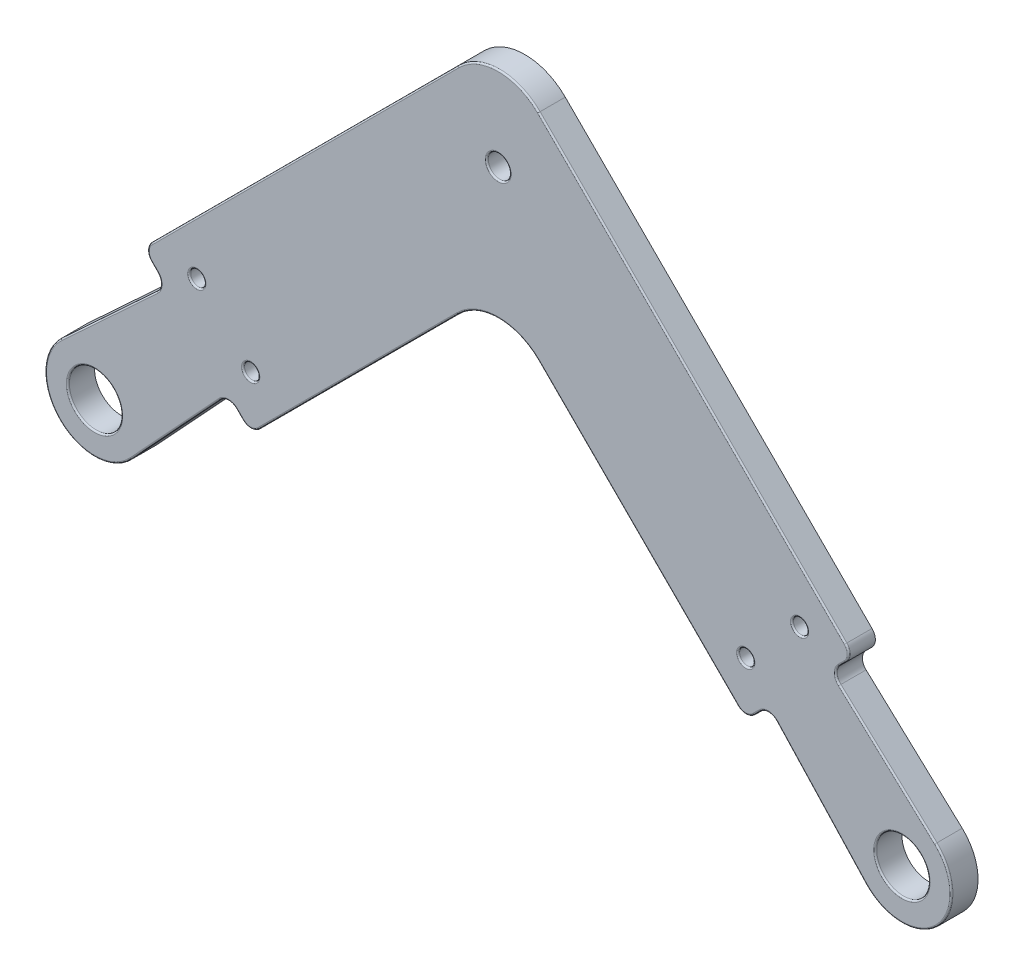
SolidWorks part; units mm, degrees
ref_plane "Front Plane" through (0, 0, 0) normal (0, 0, 1) x (1, 0, 0)
ref_plane "Top Plane" through (0, 0, 0) normal (0, 1, 0) x (1, 0, 0)
ref_plane "Right Plane" through (0, 0, 0) normal (1, 0, 0) x (0, 0, -1)
sketch "Sketch1" plane through (0, 0, 0) normal (0, 0, 1) x (1, 0, 0)
  line L0 (-106.0307, 0) -> (93.9693, 0) construction
  line L1 (-106.0307, 0) -> (-6.0307, 100) construction
  line L2 (-6.0307, 100) -> (93.9693, 0) construction
  line L3 (0, 0) -> (-53.0154, 53.0154) construction
  line L4 (-46.0307, 60) -> (33.9693, 60) construction
  line L5 (-6.0307, 100) -> (-6.0307, 60) construction
  circle A0 centre (-106.0307, 0) radius 20
  circle A1 centre (0, 0) radius 20
  circle A2 centre (93.9693, 0) radius 20
  dimension "D6" = 40
  dimension "D7" = 40
  dimension "D8" = 40
  dimension "D1" = 200
  dimension "D2" = 90
  dimension "D3" = 90
  dimension "D4" = 80
  dimension "D5" = 40
sketch "Sketch2" plane through (0, 0, 0) normal (0, 0, 1) x (1, 0, 0)
  line L0 (-62.5472, 43.4835) -> (-46.0307, 60) construction
  line L2 (-106.0307, 0) -> (-6.0307, 100) construction
  line L3 (-46.0307, 60) -> (33.9693, 60) construction
  line L4 (33.9693, 60) -> (80.5342, 13.435) construction
  line L5 (-6.0307, 100) -> (93.9693, 0) construction
  line L6 (-55.4762, 36.4124) -> (-41.8886, 50)
  line L7 (-41.8886, 50) -> (29.8271, 50)
  line L8 (29.8271, 50) -> (73.4632, 6.364)
  line L9 (-69.6183, 50.5546) -> (-50.1729, 70)
  line L10 (-50.1729, 70) -> (38.1114, 70)
  line L11 (38.1114, 70) -> (87.6053, 20.5061)
  line L12 (-55.4762, 36.4124) -> (-69.6183, 50.5546)
  line L13 (87.6053, 20.5061) -> (73.4632, 6.364)
  line L14 (98.8369, 5.0305) -> (85.2636, 18.1644)
  line L15 (88.8813, -4.8075) -> (76.0143, 8.8101)
  line L16 (85.2636, 18.1644) -> (76.0143, 8.8101)
  line L17 (84.0698, 24.0416) -> (69.9276, 9.8995) construction
  line L18 (-6.0307, 100) -> (-6.0307, 60) construction
  line L19 (-9.5307, 84.85) -> (-12.0307, 70)
  line L20 (-6.0307, 70) -> (-6.0307, 82.2198) construction
  line L21 (-2.5307, 84.85) -> (-0.0307, 70)
  circle A0 centre (93.9693, 0) radius 10 construction
  circle A1 centre (93.9693, 0) radius 3.5
  arc A2 (88.8813, -4.8075) -> (98.8369, 5.0305) centre (93.9693, 0) ccw
  circle A3 centre (93.9693, 0) radius 20 construction
  circle A4 centre (73.4632, 13.435) radius 1
  circle A5 centre (80.5342, 20.5061) radius 1
  circle A6 centre (-6.0307, 60) radius 1.5
  circle A7 centre (-6.0307, 84.85) radius 1.5
  arc A8 (-2.5307, 84.85) -> (-9.5307, 84.85) centre (-6.0307, 84.85) ccw
  circle A9 centre (-53.0154, 53.0154) radius 1.5
  point P45 (-6.0307, 70)
  dimension "D4" = 20
  dimension "D5" = 7
  dimension "D6" = 3
  dimension "D8" = 5
  dimension "D9" = 2
  dimension "D10" = 2
  dimension "D13" = 3
  dimension "D14" = 3
  dimension "D16" = 2
  dimension "D18" = 3
  dimension "D1" = 10
  dimension "D3" = 27.5
  dimension "D7" = 19
  dimension "D11" = 5
  dimension "D12" = 5
  dimension "D15" = 14.85
  dimension "D17" = 6
  dimension "D2" = 10
sketch "Sketch3" plane through (0, 0, 0) normal (0, 0, 1) x (1, 0, 0)
  line L0 (-94.5203, 11.5104) -> (-53.0154, 53.0154) construction
  line L1 (-106.0307, 0) -> (-6.0307, 100) construction
  line L2 (-53.0154, 53.0154) -> (-13.435, 13.435) construction
  line L3 (0, 0) -> (-53.0154, 53.0154) construction
  line L4 (-85.5246, 6.364) -> (-53.0154, 38.8732)
  line L5 (-53.0154, 38.8732) -> (-20.5061, 6.364)
  line L6 (-99.6668, 20.5061) -> (-53.0154, 67.1575)
  line L7 (-53.0154, 67.1575) -> (-6.364, 20.5061)
  line L8 (-95.851, 10.1797) -> (-53.0154, 53.0154) construction
  line L9 (-99.6668, 20.5061) -> (-85.5246, 6.364)
  line L10 (-20.5061, 6.364) -> (-6.364, 20.5061)
  line L11 (-102.9221, 17.2507) -> (-53.0154, 67.1575) construction
  line L12 (-88.78, 3.1086) -> (-53.0154, 38.8732) construction
  line L13 (-110.4492, 4.7673) -> (-96.685, 17.5243)
  line L14 (-106.0307, 0) -> (-96.685, 9.3457) construction
  line L15 (-101.2634, -4.4185) -> (-88.5064, 9.3457)
  line L16 (0, 0) -> (-13.435, 13.435) construction
  line L17 (-4.7673, -4.4185) -> (-17.5243, 9.3457)
  line L18 (4.4185, 4.7673) -> (-9.3457, 17.5243)
  line L19 (-96.1312, 24.0416) -> (-81.9891, 9.8995) construction
  line L20 (-9.8995, 24.0416) -> (-24.0416, 9.8995) construction
  circle A0 centre (-106.0307, 0) radius 10 construction
  circle A1 centre (-106.0307, 0) radius 3.5
  circle A2 centre (0, 0) radius 10 construction
  circle A4 centre (93.9693, 0) radius 10 construction
  circle A6 centre (0, 0) radius 3.5
  circle A7 centre (93.9693, 0) radius 3.5
  circle A8 centre (-106.0307, 0) radius 6.5
  circle A9 centre (0, 0) radius 6.5
  circle A10 centre (93.9693, 0) radius 6.5
  circle A11 centre (-92.5957, 20.5061) radius 1
  circle A12 centre (-85.5246, 13.435) radius 1
  circle A13 centre (-13.435, 20.5061) radius 1
  circle A14 centre (-20.5061, 13.435) radius 1
  circle A16 centre (-53.0154, 53.0154) radius 1.5 construction
  circle A17 centre (-53.0154, 53.0154) radius 1.5
  dimension "D1" = 20
  dimension "D2" = 20
  dimension "D3" = 20
  dimension "D4" = 7
  dimension "D5" = 7
  dimension "D6" = 7
  dimension "D7" = 3
  dimension "D8" = 3
  dimension "D9" = 3
  dimension "D14" = 2
  dimension "D15" = 2
  dimension "D16" = 2
  dimension "D17" = 2
  dimension "D10" = 10
  dimension "D12" = 19
  dimension "D13" = 19
  dimension "D18" = 5
  dimension "D19" = 5
  dimension "D20" = 5
  dimension "D21" = 5
  dimension "D22" = 5
  dimension "D23" = 5
  dimension "D11" = 10
sketch "Sketch4" plane through (0, 0, 0) normal (0, 0, 1) x (1, 0, 0)
  line L0 (-62.7556, 93.8025) -> (52.2444, 93.8025)
  line L1 (52.2444, 93.8025) -> (52.2444, 83.8025)
  line L2 (52.2444, 83.8025) -> (38.1114, 70)
  line L3 (-50.1729, 70) -> (38.1114, 70) construction
  line L4 (38.1114, 70) -> (-54.4235, 70)
  line L5 (-54.4235, 70) -> (-62.7556, 83.8025)
  line L6 (-62.7556, 83.8025) -> (-62.7556, 93.8025)
  line L7 (-2.0307, 60) -> (-2.0307, 70)
  line L8 (-10.0307, 60) -> (-10.0307, 70)
  line L9 (-28.5307, 85.3025) -> (16.4693, 85.3025) construction
  line L10 (-6.0307, 100) -> (-6.0307, 60) construction
  line L12 (-28.5307, 89.8025) -> (16.4693, 89.8025)
  line L13 (-28.5307, 80.8025) -> (16.4693, 80.8025)
  circle A0 centre (-6.0307, 60) radius 1.5 construction
  circle A1 centre (-6.0307, 60) radius 1.5
  arc A2 (-10.0307, 60) -> (-2.0307, 60) centre (-6.0307, 60) ccw
  circle A4 centre (-6.0307, 60) radius 4 construction
  arc A5 (-28.5307, 89.8025) -> (-28.5307, 80.8025) centre (-28.5307, 85.3025) ccw
  arc A6 (16.4693, 80.8025) -> (16.4693, 89.8025) centre (16.4693, 85.3025) ccw
  point P18 (-2.0307, 60)
  point P24 (-6.0307, 85.3025)
  dimension "D1" = 115
  dimension "D2" = 10
  dimension "D4" = 45
  dimension "D5" = 9
  dimension "D6" = 4
  dimension "D3" = 2.5
sketch "Sketch5" plane through (0, 0, 0) normal (0, 0, 1) x (1, 0, 0)
  line L0 (4.4185, 4.7673) -> (-9.3457, 17.5243) construction
  line L1 (-4.7673, -4.4185) -> (-17.5243, 9.3457) construction
  line L2 (-101.2634, -4.4185) -> (-88.5064, 9.3457) construction
  line L3 (-110.4492, 4.7673) -> (-96.685, 17.5243) construction
  line L4 (4.4185, 4.7673) -> (-9.3457, 17.5243)
  line L5 (-4.7673, -4.4185) -> (-17.5243, 9.3457)
  line L6 (-85.5246, 6.364) -> (-53.0154, 38.8732)
  line L7 (-53.0154, 38.8732) -> (-20.5061, 6.364)
  line L8 (-20.5061, 6.364) -> (-6.364, 20.5061)
  line L9 (-6.364, 20.5061) -> (-53.0154, 67.1575)
  line L10 (-53.0154, 67.1575) -> (-99.6668, 20.5061)
  line L11 (-99.6668, 20.5061) -> (-85.5246, 6.364)
  line L12 (-85.5246, 6.364) -> (-53.0154, 38.8732)
  line L13 (-53.0154, 38.8732) -> (-20.5061, 6.364)
  line L14 (-20.5061, 6.364) -> (-17.5243, 9.3457)
  line L15 (-6.364, 20.5061) -> (-53.0154, 67.1575)
  line L16 (-53.0154, 67.1575) -> (-99.6668, 20.5061)
  line L17 (-99.6668, 20.5061) -> (-96.685, 17.5243)
  line L18 (-101.2634, -4.4185) -> (-88.5064, 9.3457)
  line L19 (-110.4492, 4.7673) -> (-96.685, 17.5243)
  line L20 (-88.5064, 9.3457) -> (-85.5246, 6.364)
  line L21 (-9.3457, 17.5243) -> (-6.364, 20.5061)
  circle A3 centre (0, 0) radius 6.5
  arc A4 (-4.7673, -4.4185) -> (4.4185, 4.7673) centre (0, 0) ccw
  circle A5 centre (-106.0307, 0) radius 6.5
  arc A6 (-110.4492, 4.7673) -> (-101.2634, -4.4185) centre (-106.0307, 0) ccw
  circle A9 centre (0, 0) radius 3.5
  circle A10 centre (0, 0) radius 3.5
  circle A11 centre (-106.0307, 0) radius 3.5
  circle A12 centre (-106.0307, 0) radius 3.5
  circle A13 centre (-92.5957, 20.5061) radius 1
  circle A14 centre (-92.5957, 20.5061) radius 1
  circle A15 centre (-53.0154, 53.0154) radius 1.5
  circle A16 centre (-53.0154, 53.0154) radius 1.5
  circle A17 centre (-20.5061, 13.435) radius 1
  circle A18 centre (-20.5061, 13.435) radius 1
  circle A19 centre (-13.435, 20.5061) radius 1
  circle A20 centre (-13.435, 20.5061) radius 1
  circle A21 centre (-85.5246, 13.435) radius 1
  circle A22 centre (-85.5246, 13.435) radius 1
  dimension "D2" = 0
  dimension "D3" = 0
  dimension "D5" = 0
  dimension "D6" = 0
  dimension "D7" = 0
  dimension "D8" = 0
  dimension "D9" = 0
  dimension "D10" = 0
  dimension "D11" = 0
  dimension "D12" = 0
extrude "Boss-Extrude1" add sketch "Sketch5" along normal blind 3.5
fillet "Fillet1" radius 7.5 2 edges at (-53.0154, 38.8732, 1.75) (-53.0154, 67.1575, 1.75)
fillet "Fillet2" radius 1.5 8 edges at (-99.6668, 20.5061, 1.75) (-96.685, 17.5243, 1.75) (-85.5246, 6.364, 1.75) (-88.5064, 9.3457, 1.75) (-20.5061, 6.364, 1.75) (-17.5243, 9.3457, 1.75) (-9.3457, 17.5243, 1.75) (-6.364, 20.5061, 1.75)
fillet "Fillet3" radius 0.2 31 edges at (-84.5246, 13.435, 3.5) (-19.5061, 13.435, 3.5) (-91.5957, 20.5061, 3.5) (3.5, 0, 3.5) (-53.0154, 64.0509, 3.5) (-27.5683, 41.7105, 3.5) (-6.9853, 20.5061, 3.5) (-7.8343, 19.0357, 3.5) (-8.6831, 17.5369, 3.5) (-1.8923, 10.6163, 3.5) (4.5962, -4.5962, 3.5) (-10.6163, 1.8923, 3.5) (-17.5369, 8.6831, 3.5) (-19.0357, 7.8343, 3.5) (-20.5061, 6.9853, 3.5) (-34.6394, 20.4973, 3.5) (-53.0154, 35.7666, 3.5) (-71.3913, 20.4973, 3.5) (-85.5246, 6.9853, 3.5) (-86.995, 7.8343, 3.5) (-88.4938, 8.6831, 3.5) (-95.4145, 1.8923, 3.5) (-110.6269, -4.5962, 3.5) (-104.1384, 10.6163, 3.5) (-97.3476, 17.5369, 3.5) (-98.1964, 19.0357, 3.5) (-99.0454, 20.5061, 3.5) (-78.4624, 41.7105, 3.5) (-102.5307, 0, 3.5) (-51.5154, 53.0154, 3.5) (-12.435, 20.5061, 3.5)
